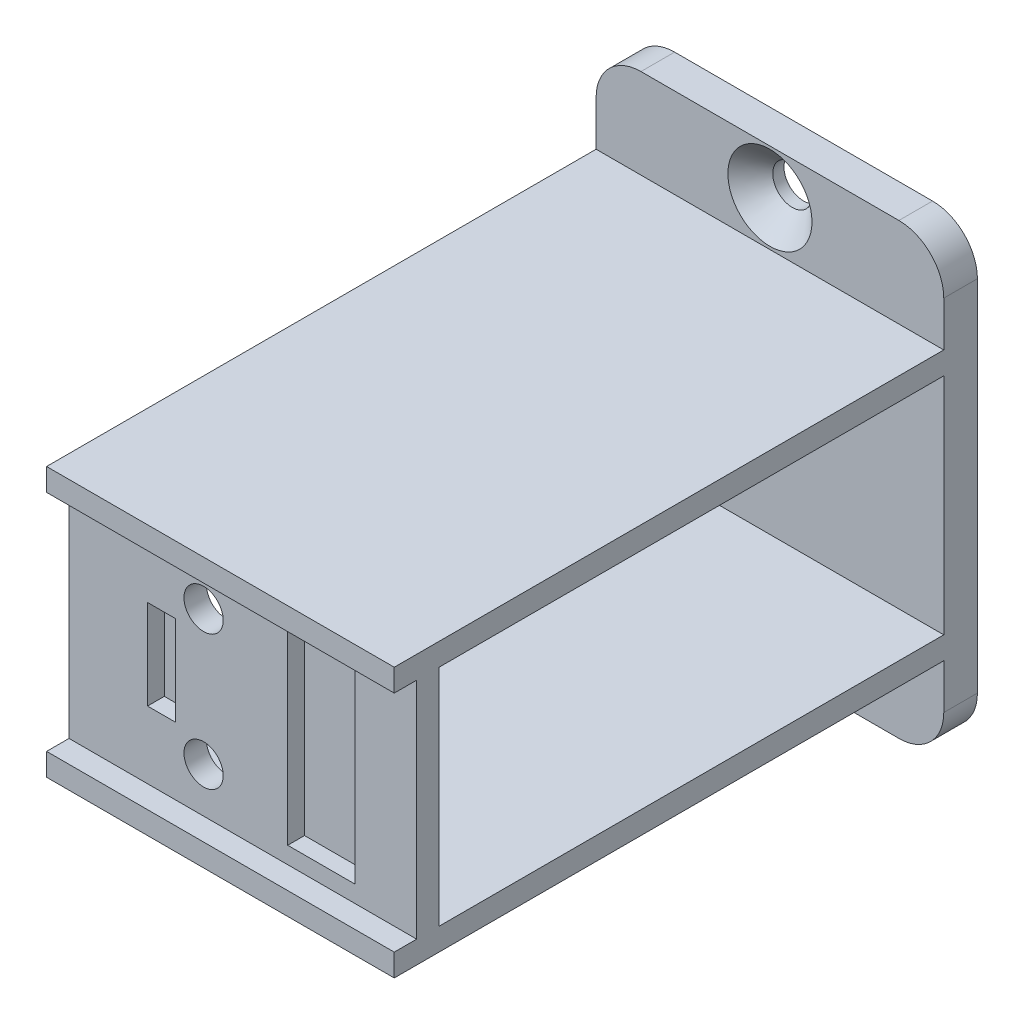
SolidWorks part; units mm, degrees
ref_plane "Front Plane" through (0, 0, 0) normal (0, 0, 1) x (1, 0, 0)
ref_plane "Top Plane" through (0, 0, 0) normal (0, 1, 0) x (1, 0, 0)
ref_plane "Right Plane" through (0, 0, 0) normal (1, 0, 0) x (0, 0, -1)
sketch "Sketch1" plane through (0, 0, 0) normal (0, 0, 1) x (1, 0, 0)
  line L1 (0, 0) -> (31, 0)
  line L2 (0, 0) -> (0, 24)
  line L3 (0, 24) -> (31, 24)
  line L4 (31, 0) -> (31, 24)
  dimension "D1" = 31
  dimension "D2" = 24
extrude "Boss-Extrude1" add sketch "Sketch1" along normal blind 2
sketch "Sketch2" plane through (0, 0, 2) normal (0, 0, 1) x (1, 0, 0)
  line L0 (31, 0) -> (31, 24) construction
  line L1 (0, 24) -> (31, 24)
  line L2 (0, 24) -> (0, 22)
  line L3 (0, 22) -> (31, 22)
  line L4 (31, 24) -> (31, 22)
  line L6 (0, 0) -> (31, 0)
  line L7 (0, 0) -> (0, 2)
  line L8 (0, 2) -> (31, 2)
  line L9 (31, 0) -> (31, 2)
  dimension "D1" = 2
  dimension "D2" = 2
extrude "Boss-Extrude2" add sketch "Sketch2" along normal blind 2
sketch "Sketch4" plane through (0, 0, 2) normal (0, 0, 1) x (1, 0, 0)
  line L0 (31, 2) -> (0, 2) construction
  line L1 (0, 22) -> (0, 2) construction
  circle A0 centre (12, 18) radius 1.75
  circle A1 centre (12, 6) radius 1.75
  dimension "D1" = 12
  dimension "D2" = 3.5
  dimension "D3" = 3.5
  dimension "D5" = 12
  dimension "D6" = 12
  dimension "D4" = 4
extrude "Cut-Extrude1" cut sketch "Sketch4" against normal blind 3
sketch "Sketch5" plane through (0, 0, 2) normal (0, 0, 1) x (1, 0, 0)
  line L0 (0, 22) -> (0, 2) construction
  line L1 (7, 16) -> (9.5, 16)
  line L2 (7, 16) -> (7, 8)
  line L3 (7, 8) -> (9.5, 8)
  line L4 (9.5, 16) -> (9.5, 8)
  line L5 (0, 22) -> (31, 22) construction
  line L6 (31, 2) -> (0, 2) construction
  line L7 (19.5, 20.5) -> (25.5, 20.5)
  line L8 (19.5, 20.5) -> (19.5, 3.5)
  line L9 (19.5, 3.5) -> (25.5, 3.5)
  line L10 (25.5, 20.5) -> (25.5, 3.5)
  line L11 (0, 22) -> (31, 22) construction
  circle A0 centre (12, 18) radius 1.75 construction
  dimension "D7" = 7.5
  dimension "D1" = 2.5
  dimension "D2" = 7
  dimension "D3" = 8
  dimension "D4" = 6
  dimension "D5" = 1.5
  dimension "D6" = 1.5
  dimension "D8" = 6
extrude "Cut-Extrude2" cut sketch "Sketch5" against normal blind 1.5
sketch "Sketch6" plane through (0, 0, 0) normal (0, 0, -1) x (-1, 0, 0)
  line L0 (0, 24) -> (0, 0) construction
  line L1 (-31, 24) -> (0, 24)
  line L2 (-31, 24) -> (-31, 22)
  line L3 (-31, 22) -> (0, 22)
  line L4 (0, 24) -> (0, 22)
  line L6 (-31, 0) -> (0, 0)
  line L7 (-31, 0) -> (-31, 2)
  line L8 (-31, 2) -> (0, 2)
  line L9 (0, 0) -> (0, 2)
  dimension "D1" = 2
  dimension "D2" = 2
extrude "Boss-Extrude4" add sketch "Sketch6" along normal blind 48
sketch "Sketch8" plane through (0, 0, 0) normal (0, -1, 0) x (1, 0, 0)
  line L0 (31, 4) -> (31, -48) construction
  line L1 (0, -48) -> (31, -48)
  line L2 (0, -48) -> (0, -45)
  line L3 (0, -45) -> (31, -45)
  line L4 (31, -48) -> (31, -45)
  dimension "D1" = 3
extrude "Boss-Extrude5" add sketch "Sketch8" against normal blind 40 from offset 8
sketch "Sketch9" plane through (0, 0, -45) normal (0, 0, 1) x (1, 0, 0)
  line L0 (0, 0) -> (0, -8) construction
  line L1 (31, -8) -> (0, -8) construction
  line L2 (0, 32) -> (0, 24) construction
  line L3 (31, 32) -> (0, 32) construction
  circle A0 centre (15.5, 28) radius 1.75
  circle A1 centre (15.5, -4) radius 1.75
  dimension "D1" = 3.5
  dimension "D2" = 15.5
  dimension "D3" = 4
  dimension "D4" = 15.5
  dimension "D5" = 4
  dimension "D6" = 3.5
extrude "Cut-Extrude3" cut sketch "Sketch9" against normal blind 38
chamfer "Chamfer1" distance 2 angle 45 2 edges at (17.25, -4, -45) (17.25, 28, -45)
fillet "Fillet1" radius 4 4 edges at (31, -8, -46.5) (0, -8, -46.5) (31, 32, -46.5) (0, 32, -46.5)
sketch "Sketch10" plane through (0, 0, 0) normal (0, -1, 0) x (1, 0, 0)
  line L0 (0, 4) -> (0, -45) construction
  circle A0 centre (5, -10) radius 1.5
  circle A1 centre (5, -35) radius 1.5
  dimension "D1" = 5
  dimension "D2" = 5
  dimension "D3" = 10
  dimension "D4" = 10
  dimension "D5" = 3
  dimension "D6" = 3
extrude "Cut-Extrude4" cut sketch "Sketch10" against normal blind 5
